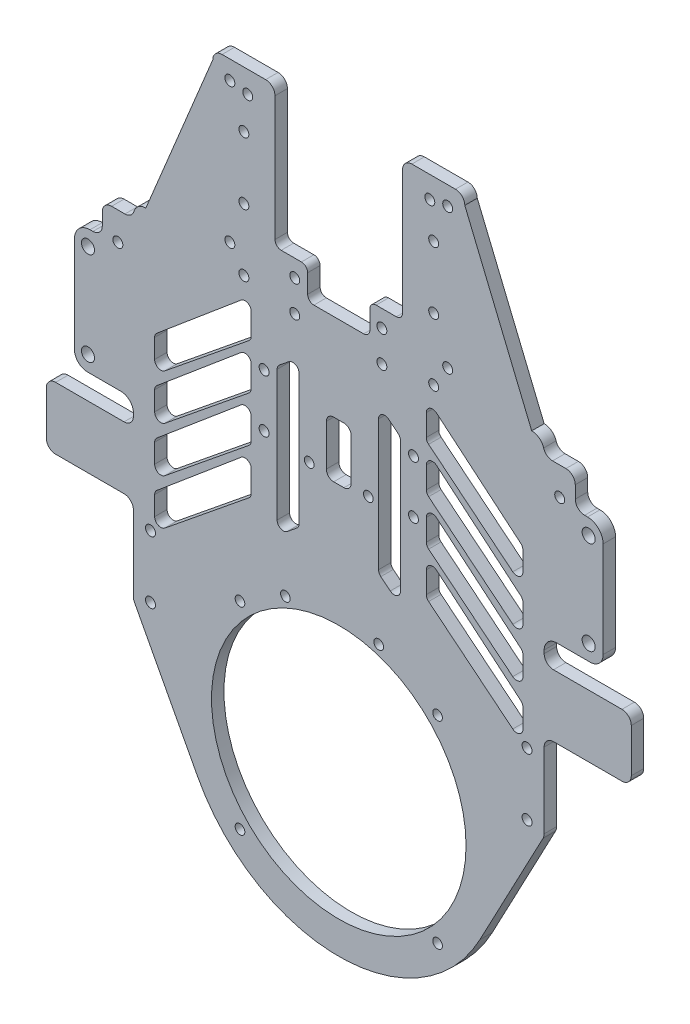
SolidWorks part; units mm, degrees
material "6061 合金"
ref_plane "前视基准面" through (0, 0, 0) normal (0, 0, 1) x (1, 0, 0)
ref_plane "上视基准面" through (0, 0, 0) normal (0, 1, 0) x (1, 0, 0)
ref_plane "右视基准面" through (0, 0, 0) normal (1, 0, 0) x (0, 0, -1)
sketch "草图1" plane through (0, 0, 0) normal (0, 0, 1) x (1, 0, 0)
  line L0 (-66, 126) -> (66, 126)
  line L1 (66, 126) -> (66, 15.1)
  line L2 (66, 15.1) -> (45.3153, -23.9831)
  line L3 (-45.3153, -23.9831) -> (-66, 15.1)
  line L4 (-66, 15.1) -> (-66, 126)
  line L5 (0, 143.651) -> (0, -77.7988) construction
  line L6 (-17.1531, 40.4102) -> (0, 0) construction
  line L7 (0, 0) -> (12.8351, 41.9818) construction
  line L8 (-31.7491, 31.7491) -> (0, 0) construction
  line L9 (-24.2152, 81.5) -> (25.2173, 81.5) construction
  line L10 (-29.945, 120.5) -> (27.106, 120.5) construction
  arc A0 (45.3153, -23.9831) -> (-45.3153, -23.9831) centre (0, 0) cw
  circle A1 centre (0, 0) radius 40.9
  circle A2 centre (0, 0) radius 44.9 construction
  circle A3 centre (-31.7491, 31.7491) radius 1.55
  circle A4 centre (-17.1531, 40.4102) radius 1.55
  circle A5 centre (12.8351, 41.9818) radius 1.55
  circle A6 centre (31.7491, 31.7491) radius 1.55
  circle A7 centre (31.7491, -31.7491) radius 1.55
  circle A8 centre (-31.7491, -31.7491) radius 1.55
  circle A9 centre (-9.5, 81.5) radius 1.55
  circle A10 centre (9.5, 81.5) radius 1.55
  circle A11 centre (-14.15, 120.5) radius 1.6
  circle A12 centre (13.85, 120.5) radius 1.6
  point P27 (0, 0)
  dimension "D3" = 81.8
  dimension "D4" = 89.8
  dimension "D7" = 17
  dimension "D11" = 3.1
  dimension "D14" = 63.4982
  dimension "D15" = 44.9
  dimension "D17" = 9.5
  dimension "D20" = 3.2
  dimension "D21" = 14.15
  dimension "D1" = 132
  dimension "D2" = 110.9
  dimension "D5" = 126
  dimension "D6" = 152.11
  dimension "D8" = 40
  dimension "D9" = 43.9
  dimension "D10" = 43.9
  dimension "D13" = 45
  dimension "D16" = 81.5
  dimension "D18" = 9.5
  dimension "D19" = 5.5
  dimension "D22" = 13.85
  dimension "D12" = 4
extrude "凸台-拉伸1" add sketch "草图1" along normal blind 4
sketch "草图2" plane through (0, 0, 4) normal (0, 0, 1) x (1, 0, 0)
  line L0 (-66, 111) -> (-79.95, 111)
  line L1 (-66, 126) -> (-66, 15.1) construction
  line L2 (-84.95, 106) -> (-84.95, 75.2)
  line L3 (-80.75, 71) -> (-66, 71)
  line L4 (-66, 71) -> (-66, 111)
  line L5 (0, 118.3019) -> (0, -51.4362) construction
  line L6 (66, 126) -> (-66, 126) construction
  line L7 (66, 71) -> (66, 111)
  line L8 (80.75, 71) -> (66, 71)
  line L9 (84.95, 106) -> (84.95, 75.2)
  line L10 (66, 111) -> (79.95, 111)
  circle A0 centre (-80.6, 106) radius 2.1
  circle A1 centre (-80.6, 76) radius 2.1
  arc A2 (-84.95, 106) -> (-79.95, 111) centre (-79.95, 106) cw
  arc A3 (-84.95, 75.2) -> (-80.75, 71) centre (-80.75, 75.2) ccw
  arc A4 (84.95, 75.2) -> (80.75, 71) centre (80.75, 75.2) cw
  arc A5 (84.95, 106) -> (79.95, 111) centre (79.95, 106) ccw
  circle A6 centre (80.3, 76) radius 2.1
  circle A7 centre (80.3, 106) radius 2.1
  point P18 (-84.95, 111)
  point P21 (-84.95, 71)
  point P34 (84.95, 71)
  point P35 (84.95, 111)
  dimension "D3" = 4.2
  dimension "D6" = 4.35
  dimension "D9" = 5
  dimension "D10" = 4.2
  dimension "D4" = 30
  dimension "D8" = 4.35
  dimension "D12" = 30
  dimension "D13" = 5
  dimension "D14" = 4.2
  dimension "D15" = 4.2
  dimension "D16" = 4.65
  dimension "D17" = 4.65
  dimension "D2" = 40
  dimension "D5" = 5
  dimension "D7" = 15
  dimension "D11" = 169.9
extrude "凸台-拉伸2" add sketch "草图2" against normal blind 4
sketch "草图3" plane through (0, 0, 4) normal (0, 0, 1) x (1, 0, 0)
  line L0 (0, 115.5232) -> (0, -53.75) construction
  line L13 (-4, 95.6433) -> (-4, 82.3567)
  line L14 (-1.6433, 80) -> (1.6433, 80)
  line L15 (4, 82.3567) -> (4, 95.6433)
  line L16 (1.6433, 98) -> (-1.6433, 98)
  line L32 (84.95, 75.2) -> (84.95, 106) construction
  line L33 (66, 126) -> (-66, 126) construction
  line L40 (-31.4189, 115.6719) -> (-58.4619, 92.9442)
  line L41 (-59.1752, 91.4131) -> (-59.1752, 85.2814)
  line L42 (-55.9148, 83.7285) -> (-28.8718, 105.6783)
  line L43 (-28.1322, 107.2311) -> (-28.1322, 114.1408)
  line L44 (-28.1322, 92.6485) -> (-28.1322, 99.5581)
  line L45 (-31.4189, 101.0892) -> (-58.4619, 78.3615)
  line L46 (-55.9148, 69.1458) -> (-28.8718, 91.0956)
  line L47 (-59.1752, 76.8304) -> (-59.1752, 70.6987)
  line L48 (-28.1322, 78.0658) -> (-28.1322, 84.9755)
  line L49 (-31.4189, 86.5065) -> (-58.4619, 63.7788)
  line L50 (-55.9148, 54.5632) -> (-28.8718, 76.5129)
  line L51 (-59.1752, 62.2477) -> (-59.1752, 56.116)
  line L52 (-28.1322, 63.4831) -> (-28.1322, 70.3928)
  line L53 (-31.4189, 71.9239) -> (-58.4619, 49.1961)
  line L54 (-55.9148, 39.9805) -> (-28.8718, 61.9302)
  line L55 (-59.1752, 47.665) -> (-59.1752, 41.5333)
  line L56 (-16.0321, 106.2463) -> (-19.0746, 103.7769)
  line L57 (-19.8142, 102.224) -> (-19.8142, 60.2677)
  line L58 (-16.5538, 58.7148) -> (-13.5113, 61.1843)
  line L59 (-12.7717, 62.7371) -> (-12.7717, 104.6934)
  line L60 (12.7717, 62.7371) -> (12.7717, 104.6934)
  line L61 (16.5538, 58.7148) -> (13.5113, 61.1843)
  line L62 (19.8142, 102.224) -> (19.8142, 60.2677)
  line L63 (16.0321, 106.2463) -> (19.0746, 103.7769)
  line L64 (59.1752, 47.665) -> (59.1752, 41.5333)
  line L65 (55.9148, 39.9805) -> (28.8718, 61.9302)
  line L66 (31.4189, 71.9239) -> (58.4619, 49.1961)
  line L67 (28.1322, 63.4831) -> (28.1322, 70.3928)
  line L68 (59.1752, 62.2477) -> (59.1752, 56.116)
  line L69 (55.9148, 54.5632) -> (28.8718, 76.5129)
  line L70 (31.4189, 86.5065) -> (58.4619, 63.7788)
  line L71 (28.1322, 78.0658) -> (28.1322, 84.9755)
  line L72 (59.1752, 76.8304) -> (59.1752, 70.6987)
  line L73 (55.9148, 69.1458) -> (28.8718, 91.0956)
  line L74 (31.4189, 101.0892) -> (58.4619, 78.3615)
  line L75 (28.1322, 92.6485) -> (28.1322, 99.5581)
  line L76 (28.1322, 107.2311) -> (28.1322, 114.1408)
  line L77 (55.9148, 83.7285) -> (28.8718, 105.6783)
  line L78 (59.1752, 91.4131) -> (59.1752, 85.2814)
  line L79 (31.4189, 115.6719) -> (58.4619, 92.9442)
  circle A9 centre (0, 0) radius 40.9 construction
  arc A10 (4, 95.6433) -> (1.6433, 98) centre (1.6433, 95.6433) ccw
  arc A11 (4, 82.3567) -> (1.6433, 80) centre (1.6433, 82.3567) cw
  arc A12 (-1.6433, 80) -> (-4, 82.3567) centre (-1.6433, 82.3567) cw
  arc A13 (-4, 95.6433) -> (-1.6433, 98) centre (-1.6433, 95.6433) cw
  arc A35 (-16.0321, 106.2463) -> (-12.7717, 104.6934) centre (-14.7717, 104.6934) cw
  arc A36 (-19.0746, 103.7769) -> (-19.8142, 102.224) centre (-17.8142, 102.224) ccw
  arc A37 (-13.5113, 61.1843) -> (-12.7717, 62.7371) centre (-14.7717, 62.7371) ccw
  arc A38 (-19.8142, 60.2677) -> (-16.5538, 58.7148) centre (-17.8142, 60.2677) ccw
  arc A39 (-55.9148, 39.9805) -> (-59.1752, 41.5333) centre (-57.1752, 41.5333) cw
  arc A40 (-58.4619, 49.1961) -> (-59.1752, 47.665) centre (-57.1752, 47.665) ccw
  arc A41 (-28.1322, 63.4831) -> (-28.8718, 61.9302) centre (-30.1322, 63.4831) cw
  arc A42 (-28.1322, 70.3928) -> (-31.4189, 71.9239) centre (-30.1322, 70.3928) ccw
  arc A43 (-55.9148, 54.5632) -> (-59.1752, 56.116) centre (-57.1752, 56.116) cw
  arc A44 (-58.4619, 63.7788) -> (-59.1752, 62.2477) centre (-57.1752, 62.2477) ccw
  arc A45 (-28.1322, 78.0658) -> (-28.8718, 76.5129) centre (-30.1322, 78.0658) cw
  arc A46 (-28.1322, 84.9755) -> (-31.4189, 86.5065) centre (-30.1322, 84.9755) ccw
  arc A47 (-58.4619, 78.3615) -> (-59.1752, 76.8304) centre (-57.1752, 76.8304) ccw
  arc A48 (-55.9148, 69.1458) -> (-59.1752, 70.6987) centre (-57.1752, 70.6987) cw
  arc A49 (-28.1322, 92.6485) -> (-28.8718, 91.0956) centre (-30.1322, 92.6485) cw
  arc A50 (-28.1322, 99.5581) -> (-31.4189, 101.0892) centre (-30.1322, 99.5581) ccw
  arc A51 (-59.1752, 85.2814) -> (-55.9148, 83.7285) centre (-57.1752, 85.2814) ccw
  arc A52 (-58.4619, 92.9442) -> (-59.1752, 91.4131) centre (-57.1752, 91.4131) ccw
  arc A53 (-28.8718, 105.6783) -> (-28.1322, 107.2311) centre (-30.1322, 107.2311) ccw
  arc A54 (-31.4189, 115.6719) -> (-28.1322, 114.1408) centre (-30.1322, 114.1408) cw
  arc A55 (31.4189, 115.6719) -> (28.1322, 114.1408) centre (30.1322, 114.1408) ccw
  arc A56 (28.8718, 105.6783) -> (28.1322, 107.2311) centre (30.1322, 107.2311) cw
  arc A57 (58.4619, 92.9442) -> (59.1752, 91.4131) centre (57.1752, 91.4131) cw
  arc A58 (59.1752, 85.2814) -> (55.9148, 83.7285) centre (57.1752, 85.2814) cw
  arc A59 (28.1322, 99.5581) -> (31.4189, 101.0892) centre (30.1322, 99.5581) cw
  arc A60 (28.1322, 92.6485) -> (28.8718, 91.0956) centre (30.1322, 92.6485) ccw
  arc A61 (55.9148, 69.1458) -> (59.1752, 70.6987) centre (57.1752, 70.6987) ccw
  arc A62 (58.4619, 78.3615) -> (59.1752, 76.8304) centre (57.1752, 76.8304) cw
  arc A63 (28.1322, 84.9755) -> (31.4189, 86.5065) centre (30.1322, 84.9755) cw
  arc A64 (28.1322, 78.0658) -> (28.8718, 76.5129) centre (30.1322, 78.0658) ccw
  arc A65 (58.4619, 63.7788) -> (59.1752, 62.2477) centre (57.1752, 62.2477) cw
  arc A66 (55.9148, 54.5632) -> (59.1752, 56.116) centre (57.1752, 56.116) ccw
  arc A67 (28.1322, 70.3928) -> (31.4189, 71.9239) centre (30.1322, 70.3928) cw
  arc A68 (28.1322, 63.4831) -> (28.8718, 61.9302) centre (30.1322, 63.4831) ccw
  arc A69 (58.4619, 49.1961) -> (59.1752, 47.665) centre (57.1752, 47.665) cw
  arc A70 (55.9148, 39.9805) -> (59.1752, 41.5333) centre (57.1752, 41.5333) ccw
  arc A71 (19.8142, 60.2677) -> (16.5538, 58.7148) centre (17.8142, 60.2677) cw
  arc A72 (13.5113, 61.1843) -> (12.7717, 62.7371) centre (14.7717, 62.7371) cw
  arc A73 (19.0746, 103.7769) -> (19.8142, 102.224) centre (17.8142, 102.224) cw
  arc A74 (16.0321, 106.2463) -> (12.7717, 104.6934) centre (14.7717, 104.6934) ccw
  dimension "D1" = 4
  dimension "D6" = 2.3567
  dimension "D7" = 2
  dimension "D2" = 4
  dimension "D3" = 4
  dimension "D4" = 18
  dimension "D5" = 80
extrude "切除-拉伸1" cut sketch "草图3" against normal blind 4
fillet "圆角1" radius 4 4 edges at (-66, 71, 2) (66, 71, 2) (66, 126, 2) (-66, 126, 2)
sketch "草图4" plane through (0, 0, 4) normal (0, 0, 1) x (1, 0, 0)
  line L0 (-10, 126) -> (-10, 119)
  line L1 (62, 126) -> (-62, 126) construction
  line L2 (-10, 119) -> (10, 119)
  line L3 (10, 119) -> (10, 126)
  line L4 (10, 126) -> (-10, 126)
  line L5 (66, 111) -> (66, 122) construction
  dimension "D1" = 7
  dimension "D2" = 20
  dimension "D3" = 56
extrude "切除-拉伸2" cut sketch "草图4" against normal through all
fillet "圆角2" radius 2 4 edges at (10, 126, 2) (-10, 126, 2) (-10, 119, 2) (10, 119, 2)
sketch "草图5" plane through (0, 0, 4) normal (0, 0, 1) x (1, 0, 0)
  line L0 (-40.5, 126) -> (-40.5, 181)
  line L1 (-12, 126) -> (-62, 126) construction
  line L2 (-40.5, 181) -> (-20.5, 181)
  line L3 (-20.5, 181) -> (-20.5, 126)
  line L4 (-40.5, 126) -> (-20.5, 126)
  line L5 (0, 172.5721) -> (0, 103.5745) construction
  line L10 (20.5, 126) -> (20.5, 181)
  line L11 (62, 126) -> (12, 126) construction
  line L12 (20.5, 181) -> (40.5, 181)
  line L13 (40.5, 181) -> (40.5, 126)
  line L14 (40.5, 126) -> (20.5, 126)
  dimension "D1" = 20
  dimension "D2" = 55
  dimension "D3" = 20.5
  dimension "D4" = 20
  dimension "D5" = 55
  dimension "D6" = 20.5
extrude "凸台-拉伸3" add sketch "草图5" against normal blind 4
sketch "草图6" plane through (0, 0, 4) normal (0, 0, 1) x (1, 0, 0)
  line L0 (-40.5, 181) -> (-40.5, 126) construction
  line L2 (0, 181.9353) -> (0, 128.2449) construction
  line L3 (-20.5, 181) -> (-40.5, 181) construction
  circle A0 centre (-29.75, 177) radius 1.65
  circle A1 centre (-29.75, 143.5) radius 1.65
  circle A4 centre (29.75, 143.5) radius 1.65
  circle A5 centre (29.75, 177) radius 1.65
  dimension "D1" = 3.3
  dimension "D2" = 10.75
  dimension "D4" = 4
  dimension "D3" = 33.5
fillet "圆角3" radius 3 4 edges at (40.5, 126, 2) (40.5, 181, 2) (-40.5, 126, 2) (-40.5, 181, 2)
sketch "草图7" plane through (0, 0, 4) normal (0, 0, 1) x (1, 0, 0)
  line L0 (0, 0) -> (0, 119) construction
  line L1 (-8, 119) -> (8, 119) construction
  line L2 (-30.5, 163) -> (-30.5, 130.7752) construction
  line L5 (-43.5, 126) -> (-62, 126) construction
  circle A0 centre (-30.5, 163) radius 1.6
  circle A1 centre (-30.5, 143) radius 1.6
  circle A2 centre (-30.5, 123) radius 1.6
  circle A3 centre (30.5, 163) radius 1.6
  circle A4 centre (30.5, 123) radius 1.6
  circle A5 centre (30.5, 143) radius 1.6
  dimension "D1" = 3.2
  dimension "D2" = 20
  dimension "D3" = 20
  dimension "D4" = 61
  dimension "D5" = 3
extrude "切除-拉伸4" cut sketch "草图7" against normal blind 10
sketch "草图8" plane through (0, 0, 4) normal (0, 0, 1) x (1, 0, 0)
  line L2 (24, 83) -> (-24, 83) construction
  line L3 (24, 83) -> (24, 100) construction
  line L4 (24, 100) -> (-24, 100) construction
  line L5 (-24, 83) -> (-24, 100) construction
  line L6 (24, 83) -> (-24, 100) construction
  line L7 (24, 100) -> (-24, 83) construction
  line L8 (37.5, 181) -> (20.5, 181) construction
  line L9 (0, 0) -> (0, 123.2843)
  circle A0 centre (-24, 100) radius 1.6
  circle A1 centre (24, 100) radius 1.6
  circle A2 centre (24, 83) radius 1.6
  circle A3 centre (-24, 83) radius 1.6
  point P0 (0, 91.5)
  dimension "D1" = 17
  dimension "D2" = 48
  dimension "D4" = 3.2
  dimension "D3" = 81
extrude "切除-拉伸7" cut sketch "草图8" against normal blind 24 contours A0 | A3 | A2 | A1
sketch "草图9" plane through (0, 0, 4) normal (0, 0, 1) x (1, 0, 0)
  line L0 (0, 0) -> (0, 119) construction
  line L1 (66, 111) -> (76, 111)
  line L2 (66, 111) -> (66, 121)
  line L3 (66, 121) -> (76, 121)
  line L4 (76, 111) -> (76, 121)
  line L5 (-8, 119) -> (8, 119) construction
  line L6 (-66, 121) -> (-76, 121)
  line L7 (-76, 111) -> (-76, 121)
  line L8 (-66, 111) -> (-76, 111)
  line L9 (-66, 111) -> (-66, 121)
  dimension "D1" = 10
  dimension "D2" = 10
extrude "凸台-拉伸4" add sketch "草图9" against normal blind 4
fillet "圆角5" radius 3 6 edges at (-76, 111, 2) (-76, 121, 2) (-66, 121, 2) (66, 121, 2) (76, 121, 2) (76, 111, 2)
sketch "草图10" plane through (0, 0, 4) normal (0, 0, 1) x (1, 0, 0)
  line L0 (-76, 118) -> (-76, 114) construction
  line L1 (-68.7082, 121) -> (-73, 121) construction
  line L2 (0, 0) -> (0, 119) construction
  line L3 (-8, 119) -> (8, 119) construction
  circle A0 centre (-71, 112) radius 1.6
  circle A1 centre (71, 112) radius 1.6
  dimension "D1" = 3.2
  dimension "D2" = 5
  dimension "D3" = 9
extrude "切除-拉伸6" cut sketch "草图10" against normal blind 4
sketch "草图11" plane through (0, 0, 4) normal (0, 0, 1) x (1, 0, 0)
  line L0 (66, 15.1) -> (66, 67) construction
  line L1 (66, 63) -> (94, 63)
  line L2 (66, 63) -> (66, 43)
  line L3 (66, 43) -> (94, 43)
  line L4 (94, 63) -> (94, 43)
  line L5 (70, 71) -> (80.75, 71) construction
  line L6 (0, 27.3868) -> (0, -17.8221) construction
  line L7 (-66, 43) -> (-94, 43)
  line L8 (-66, 63) -> (-66, 43)
  line L9 (-66, 63) -> (-94, 63)
  line L10 (-94, 63) -> (-94, 43)
  dimension "D1" = 20
  dimension "D2" = 28
  dimension "D3" = 8
extrude "凸台-拉伸5" add sketch "草图11" against normal blind 4
fillet "圆角6" radius 3 12 edges at (-20.5, 181, 2) (20.5, 181, 2) (-94, 63, 2) (-94, 43, 2) (-66, 43, 2) (-66, 15.1, 2) (66, 15.1, 2) (66, 43, 2) (94, 43, 2) (94, 63, 2) (66, 63, 2) (-66, 63, 2)
sketch "草图13" plane through (0, 0, 4) normal (0, 0, 1) x (1, 0, 0)
  line L0 (-60.5, 152.6337) -> (-60.5, -37.2841) construction
  line L1 (-66, 40) -> (-66, 15.8449) construction
  line L2 (-91, 43) -> (-69, 43) construction
  line L3 (0, 166.4374) -> (0, -97.031) construction
  circle A0 centre (-60.5, 37) radius 1.6
  circle A1 centre (-60.5, 17) radius 1.6
  circle A2 centre (60.5, 17) radius 1.6
  circle A3 centre (60.5, 37) radius 1.6
  dimension "D2" = 3.2
  dimension "D3" = 20
  dimension "D4" = 6
  dimension "D1" = 5.5
extrude "切除-拉伸8" cut sketch "草图13" against normal blind 45
sketch "草图14" plane through (0, 0, 4) normal (0, 0, 1) x (1, 0, 0)
  line L0 (-23.5, 181) -> (-37.5, 181) construction
  line L1 (-40.5, 178) -> (-40.5, 129) construction
  line L2 (0, 181.7466) -> (0, 80.6903) construction
  circle A0 centre (-29.25, 174) radius 1.6
  circle A1 centre (29.25, 174) radius 1.6
  dimension "D1" = 3.2
  dimension "D2" = 7
  dimension "D3" = 11.25
extrude "切除-拉伸9" cut sketch "草图14" against normal blind 10
sketch "草图15" plane through (0, 0, 4) normal (0, 0, 1) x (1, 0, 0)
  line L0 (0, 152.5) -> (0, 0) construction
  line L1 (35, 130) -> (-35, 130) construction
  line L2 (35, 130) -> (35, 175) construction
  line L3 (35, 175) -> (-35, 175) construction
  line L4 (-35, 130) -> (-35, 175) construction
  line L5 (35, 130) -> (-35, 175) construction
  line L6 (35, 175) -> (-35, 130) construction
  line L7 (-23.5, 181) -> (-37.5, 181) construction
  circle A0 centre (-35, 175) radius 1.6
  circle A1 centre (35, 175) radius 1.6
  circle A2 centre (-35, 130) radius 1.6
  circle A3 centre (35, 130) radius 1.6
  point P0 (0, 152.5)
  dimension "D4" = 3.2
  dimension "D1" = 45
  dimension "D2" = 70
  dimension "D3" = 6
extrude "切除-拉伸10" cut sketch "草图15" against normal blind 10
sketch "草图16" plane through (0, 0, 4) normal (0, 0, 1) x (1, 0, 0)
  line L0 (-20.5, 136) -> (20.5, 136)
  line L1 (-14.15, 130.5) -> (-14.15, 120.5) construction
  line L2 (13.85, 120.5) -> (13.85, 130.5) construction
  line L35 (-20.5, 126) -> (-20.5, 178)
  line L36 (-23.5, 181) -> (-37.5, 181)
  line L37 (-40.5, 178) -> (-40.5, 129)
  line L38 (-43.5, 126) -> (-62, 126)
  line L39 (-68.7082, 121) -> (-73, 121)
  line L40 (-76, 118) -> (-76, 114)
  line L41 (-79, 111) -> (-79.95, 111)
  line L42 (-84.95, 106) -> (-84.95, 75.2)
  line L43 (-80.75, 71) -> (-70, 71)
  line L44 (-66, 67) -> (-66, 66)
  line L45 (-69, 63) -> (-91, 63)
  line L46 (-94, 60) -> (-94, 46)
  line L47 (-91, 43) -> (-69, 43)
  line L48 (-66, 40) -> (-66, 15.8449)
  line L49 (-65.6515, 14.4416) -> (-45.3153, -23.9831)
  line L50 (45.3153, -23.9831) -> (65.6515, 14.4416)
  line L51 (66, 15.8449) -> (66, 40)
  line L52 (69, 43) -> (91, 43)
  line L53 (94, 46) -> (94, 60)
  line L54 (91, 63) -> (69, 63)
  line L55 (66, 66) -> (66, 67)
  line L56 (70, 71) -> (80.75, 71)
  line L57 (84.95, 75.2) -> (84.95, 106)
  line L58 (79.95, 111) -> (79, 111)
  line L59 (76, 114) -> (76, 118)
  line L60 (73, 121) -> (68.7082, 121)
  line L61 (62, 126) -> (43.5, 126)
  line L62 (40.5, 129) -> (40.5, 178)
  line L63 (37.5, 181) -> (23.5, 181)
  line L64 (20.5, 178) -> (20.5, 126)
  line L65 (20.5, 126) -> (12, 126)
  line L66 (10, 124) -> (10, 121)
  line L67 (8, 119) -> (-8, 119)
  line L68 (-10, 121) -> (-10, 124)
  line L69 (-12, 126) -> (-20.5, 126)
  line L70 (-20.5, 126) -> (-20.5, 136)
  line L99 (20.5, 136) -> (20.5, 126)
  line L100 (20.5, 126) -> (12, 126)
  line L101 (10, 124) -> (10, 121)
  line L102 (8, 119) -> (-8, 119)
  line L103 (-10, 121) -> (-10, 124)
  line L104 (-12, 126) -> (-20.5, 126)
  circle A0 centre (-14.15, 130.5) radius 1.6
  circle A1 centre (13.85, 130.5) radius 1.6
  arc A35 (-20.5, 178) -> (-23.5, 181) centre (-23.5, 178) ccw
  arc A36 (-37.5, 181) -> (-40.5, 178) centre (-37.5, 178) ccw
  arc A37 (-43.5, 126) -> (-40.5, 129) centre (-43.5, 129) ccw
  arc A38 (-62, 126) -> (-65.8333, 123.1429) centre (-62, 122) ccw
  arc A39 (-68.7082, 121) -> (-65.8333, 123.1429) centre (-68.7082, 124) ccw
  arc A40 (-73, 121) -> (-76, 118) centre (-73, 118) ccw
  arc A41 (-79, 111) -> (-76, 114) centre (-79, 114) ccw
  arc A42 (-79.95, 111) -> (-84.95, 106) centre (-79.95, 106) ccw
  arc A43 (-84.95, 75.2) -> (-80.75, 71) centre (-80.75, 75.2) ccw
  arc A44 (-66, 67) -> (-70, 71) centre (-70, 67) ccw
  arc A45 (-69, 63) -> (-66, 66) centre (-69, 66) ccw
  arc A46 (-91, 63) -> (-94, 60) centre (-91, 60) ccw
  arc A47 (-94, 46) -> (-91, 43) centre (-91, 46) ccw
  arc A48 (-66, 40) -> (-69, 43) centre (-69, 40) ccw
  arc A49 (-66, 15.8449) -> (-65.6515, 14.4416) centre (-63, 15.8449) ccw
  arc A50 (-45.3153, -23.9831) -> (45.3153, -23.9831) centre (0, 0) ccw
  arc A51 (65.6515, 14.4416) -> (66, 15.8449) centre (63, 15.8449) ccw
  arc A52 (69, 43) -> (66, 40) centre (69, 40) ccw
  arc A53 (91, 43) -> (94, 46) centre (91, 46) ccw
  arc A54 (94, 60) -> (91, 63) centre (91, 60) ccw
  arc A55 (66, 66) -> (69, 63) centre (69, 66) ccw
  arc A56 (70, 71) -> (66, 67) centre (70, 67) ccw
  arc A57 (80.75, 71) -> (84.95, 75.2) centre (80.75, 75.2) ccw
  arc A58 (84.95, 106) -> (79.95, 111) centre (79.95, 106) ccw
  arc A59 (76, 114) -> (79, 111) centre (79, 114) ccw
  arc A60 (76, 118) -> (73, 121) centre (73, 118) ccw
  arc A61 (65.8333, 123.1429) -> (68.7082, 121) centre (68.7082, 124) ccw
  arc A62 (65.8333, 123.1429) -> (62, 126) centre (62, 122) ccw
  arc A63 (40.5, 129) -> (43.5, 126) centre (43.5, 129) ccw
  arc A64 (40.5, 178) -> (37.5, 181) centre (37.5, 178) ccw
  arc A65 (23.5, 181) -> (20.5, 178) centre (23.5, 178) ccw
  arc A66 (12, 126) -> (10, 124) centre (12, 124) ccw
  arc A67 (8, 119) -> (10, 121) centre (8, 121) ccw
  arc A68 (-10, 121) -> (-8, 119) centre (-8, 121) ccw
  arc A69 (-10, 124) -> (-12, 126) centre (-12, 124) ccw
  arc A101 (12, 126) -> (10, 124) centre (12, 124) ccw
  arc A102 (8, 119) -> (10, 121) centre (8, 121) ccw
  arc A103 (-10, 121) -> (-8, 119) centre (-8, 121) ccw
  arc A104 (-10, 124) -> (-12, 126) centre (-12, 124) ccw
  dimension "D3" = 3.2
  dimension "D4" = 3.2
  dimension "D5" = 10
  dimension "D2" = 17
  dimension "D6" = 10
  dimension "D1" = 0
extrude "凸台-拉伸6" add sketch "草图16" against normal blind 4
sketch "草图17" plane through (0, 0, 4) normal (0, 0, 1) x (1, 0, 0)
  line L0 (20.5, 136) -> (-20.5, 136) construction
  line L1 (10, 126) -> (-10, 126)
  line L2 (10, 126) -> (10, 136)
  line L3 (10, 136) -> (-10, 136)
  line L4 (-10, 126) -> (-10, 136)
  dimension "D1" = 20
  dimension "D2" = 10
  dimension "D3" = 10
extrude "切除-拉伸11" cut sketch "草图17" against normal blind 4
fillet "圆角7" radius 2 6 edges at (10, 126, 2) (-10, 126, 2) (-10, 136, 2) (20.5, 136, 2) (10, 136, 2) (-20.5, 136, 2)
sketch "草图18" plane through (0, 0, 0) normal (0, 0, -1) x (-1, 0, 0)
  line L0 (-40.5, 178) -> (-62, 126)
  line L1 (40.5, 178) -> (62, 126)
  line L2 (62, 126) -> (40.5, 126)
  line L3 (40.5, 126) -> (40.5, 178)
  line L4 (-40.5, 178) -> (-40.5, 126)
  line L5 (-40.5, 126) -> (-62, 126)
extrude "凸台-拉伸7" add sketch "草图18" against normal up to surface (4 mm away)
